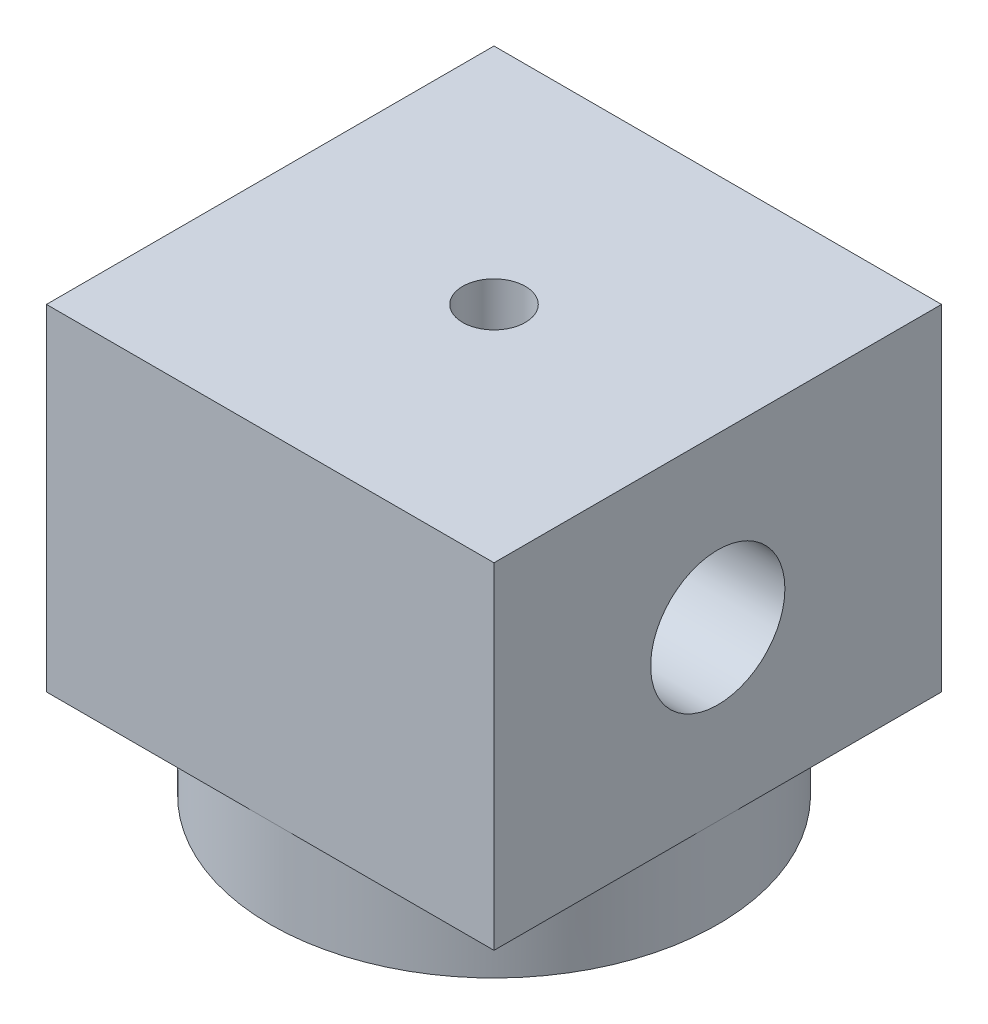
SolidWorks part; units mm, degrees
ref_plane "Front Plane" through (0, 0, 0) normal (0, 0, 1) x (1, 0, 0)
ref_plane "Top Plane" through (0, 0, 0) normal (0, 1, 0) x (1, 0, 0)
ref_plane "Right Plane" through (0, 0, 0) normal (1, 0, 0) x (0, 0, -1)
sketch "Sketch1" plane through (0, 0, 0) normal (0, 1, 0) x (1, 0, 0)
  circle A0 centre (0, 0) radius 10
  dimension "D1" = 20
extrude "Boss-Extrude1" add sketch "Sketch1" along normal blind 4
sketch "Sketch2" plane through (0, 0, 0) normal (0, -1, 0) x (1, 0, 0)
  circle A0 centre (0, 0) radius 2.45
  dimension "D1" = 4.9
extrude "Cut-Extrude1" cut sketch "Sketch2" against normal blind 2.5
sketch "Sketch3" plane through (0, 0, 0) normal (1, 0, 0) x (0, 0, -1)
  line L0 (-10, 19) -> (10, 4) construction
  line L1 (-10, 4) -> (10, 4)
  line L2 (-10, 4) -> (-10, 19)
  line L3 (-10, 19) -> (10, 19)
  line L4 (10, 4) -> (10, 19)
  circle A0 centre (0, 11.5) radius 3
  point P9 (0, 0)
  dimension "D2" = 6
  dimension "D1" = 15
extrude "Boss-Extrude2" add sketch "Sketch3" along normal mid plane 20
sketch "Sketch4" plane through (0, 19, 0) normal (0, 1, 0) x (1, 0, 0)
  circle A0 centre (0, 0) radius 1.4
  dimension "D1" = 2.8
extrude "Cut-Extrude2" cut sketch "Sketch4" against normal blind 8
